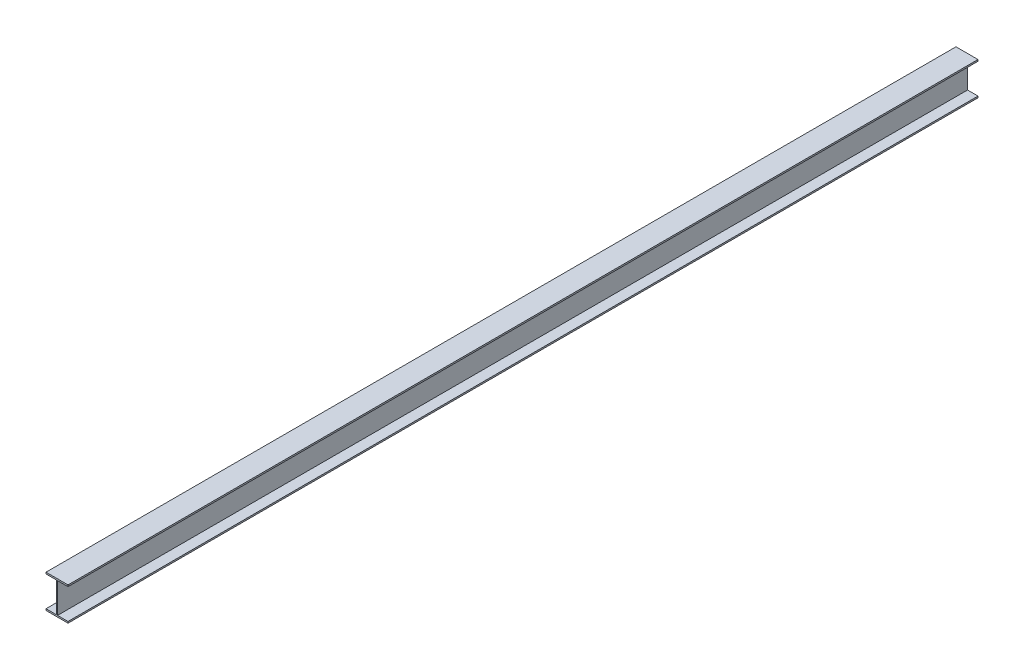
SolidWorks part; units mm, degrees
material "ASTM A992 Steel"
ref_plane "Front" through (0, 0, 0) normal (0, 0, 1) x (1, 0, 0)
ref_plane "Top" through (0, 0, 0) normal (0, 1, 0) x (1, 0, 0)
ref_plane "Right" through (0, 0, 0) normal (1, 0, 0) x (0, 0, -1)
sketch "Sketch1" plane through (0, 0, 0) normal (0, 0, 1) x (1, 0, 0)
  line L0 (0, -0.0002) -> (101.6, -0.0002)
  line L1 (101.6, -0.0002) -> (101.6, -7.1122)
  line L2 (101.6, -7.1122) -> (53.408, -7.1122)
  line L3 (53.408, -7.1122) -> (53.408, -146.0502)
  line L4 (53.408, -146.0502) -> (101.6, -146.0502)
  line L5 (101.6, -146.0502) -> (101.6, -153.1622)
  line L6 (101.6, -153.1622) -> (0, -153.1622)
  line L7 (0, -153.1622) -> (0, -146.0502)
  line L8 (0, -146.0502) -> (47.566, -146.0502)
  line L9 (47.566, -146.0502) -> (47.566, -7.1122)
  line L10 (47.566, -7.1122) -> (0, -7.1122)
  line L11 (0, -7.1122) -> (0, -0.0002)
  line L12 (50.8, -0.0002) -> (50.8, -153.1622) construction
  dimension "D1" = 5.842
  dimension "D2" = 7.112
  dimension "D3" = 7.112
  dimension "D4" = 7.112
  dimension "D5" = 153.162
  dimension "D6" = 50.8
  dimension "D7" = 50.8
  dimension "D8" = 47.566
extrude "Boss-Extrude1" add sketch "Sketch1" along normal blind 4200
sketch "Sketch2" plane through (0, -153.1622, 0) normal (0, -1, 0) x (1, 0, 0)
  line L2 (101.6, 4200) -> (101.6, 0) construction
  line L5 (101.6, 2100) -> (101.6, 2252.4)
  line L6 (101.6, 2252.4) -> (-229.7319, 2252.4)
  line L7 (-229.7319, 2000) -> (-229.7319, 2252.4)
  line L9 (101.6, 2100) -> (101.6, 1947.6)
  line L10 (101.6, 1947.6) -> (-229.7319, 1947.6)
  line L11 (-229.7319, 2000) -> (-229.7319, 1947.6)
  point P0 (101.6, 2100)
  dimension "D1" = 152.4
  dimension "D2" = 152.4
split line "Split Line1"
